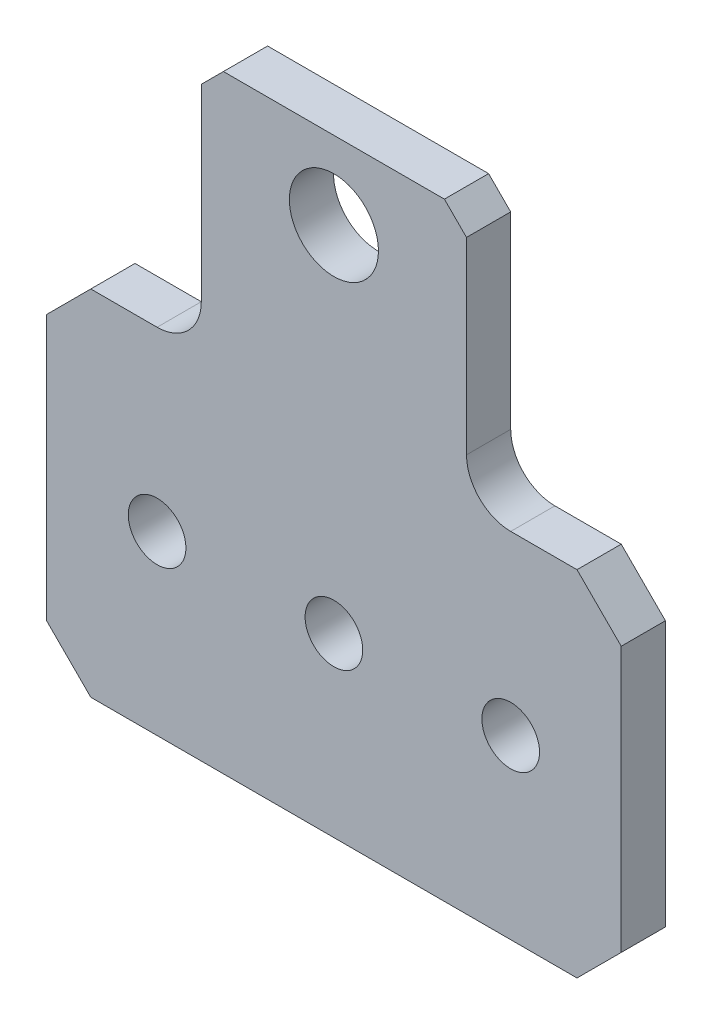
SolidWorks part; units mm, degrees
material "6063-T5"
ref_plane "Front Plane" through (0, 0, 0) normal (0, 0, 1) x (1, 0, 0)
ref_plane "Top Plane" through (0, 0, 0) normal (0, 1, 0) x (1, 0, 0)
ref_plane "Right Plane" through (0, 0, 0) normal (1, 0, 0) x (0, 0, -1)
ref_plane "Plane4" through (0, 0, 0) normal (0, 0, -1) x (-1, 0, 0)
sketch "Sketch1" plane through (0, 0, 0) normal (0, 0, -1) x (-1, 0, 0)
  line L0 (-17.4625, -15.494) -> (-20.6375, -18.669)
  line L1 (-20.6375, -18.669) -> (-20.6375, -37.719)
  line L2 (-20.6375, -37.719) -> (-17.4625, -40.894)
  line L3 (-17.4625, -40.894) -> (17.4625, -40.894)
  line L4 (17.4625, -40.894) -> (20.6375, -37.719)
  line L5 (20.6375, -37.719) -> (20.6375, -18.669)
  line L6 (20.6375, -18.669) -> (17.4625, -15.494)
  line L7 (17.4625, -15.494) -> (12.7, -15.494)
  line L8 (9.525, -12.319) -> (9.525, 1.2065)
  line L9 (9.525, 1.2065) -> (7.9375, 2.794)
  line L10 (7.9375, 2.794) -> (9.525, 4.3815)
  line L11 (9.525, 4.3815) -> (9.525, 37.719)
  line L12 (9.525, 37.719) -> (6.35, 40.894)
  line L13 (6.35, 40.894) -> (-6.35, 40.894)
  line L14 (-6.35, 40.894) -> (-9.525, 37.719)
  line L15 (-9.525, 37.719) -> (-9.525, 4.3815)
  line L16 (-9.525, 4.3815) -> (-7.9375, 2.794)
  line L17 (-7.9375, 2.794) -> (-9.525, 1.2065)
  line L18 (-9.525, 1.2065) -> (-9.525, -12.319)
  line L19 (-12.7, -15.494) -> (-17.4625, -15.494)
  arc A0 (12.7, -15.494) -> (9.525, -12.319) centre (12.7, -12.319) cw
  arc A1 (-9.525, -12.319) -> (-12.7, -15.494) centre (-12.7, -12.319) cw
  circle A2 centre (0, 35.306) radius 3.2004
  circle A3 centre (0, -2.794) radius 3.2004
  circle A4 centre (12.7, -28.194) radius 2.0701
  circle A5 centre (-12.7, -28.194) radius 2.0701
  circle A6 centre (0, -28.194) radius 2.0701
extrude "Boss-Extrude1" add sketch "Sketch1" against normal blind 3.175
sketch "Sketch2" plane through (0, 0, 3.175) normal (0, 0, 1) x (1, 0, 0)
  line L1 (-10.8454, 2.794) -> (22.2616, 2.794)
  line L2 (-10.8454, 2.794) -> (-10.8454, 48.0081)
  line L3 (-10.8454, 48.0081) -> (22.2616, 48.0081)
  line L4 (22.2616, 2.794) -> (22.2616, 48.0081)
extrude "Cut-Extrude1" cut sketch "Sketch2" against normal through all
